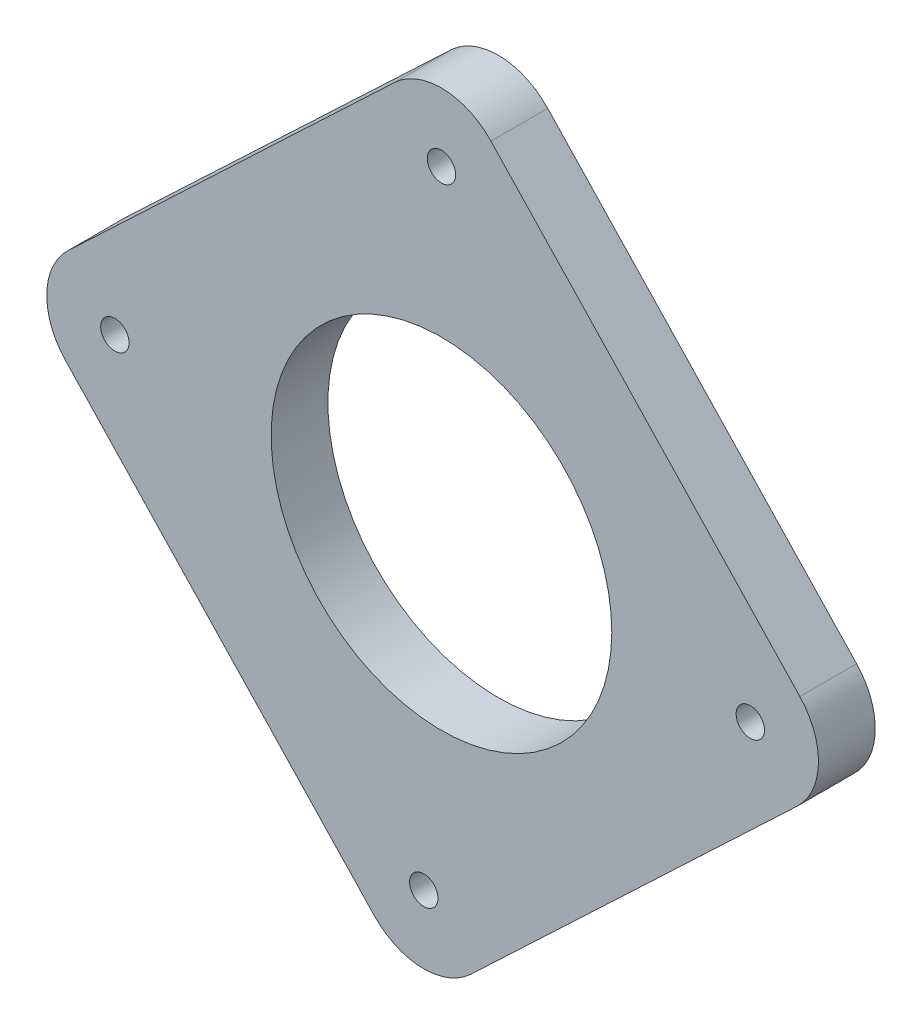
SolidWorks part; units mm, degrees
ref_plane "Front Plane" through (0, 0, 0) normal (0, 0, 1) x (1, 0, 0)
ref_plane "Top Plane" through (0, 0, 0) normal (0, 1, 0) x (1, 0, 0)
ref_plane "Right Plane" through (0, 0, 0) normal (1, 0, 0) x (0, 0, -1)
sketch "Sketch1" plane through (0, 0, 0) normal (0, 0, 1) x (1, 0, 0)
  line L0 (0, 0) -> (0, 28) construction
  line L1 (-33.1153, -3.3234) -> (-5.9149, -32.0798)
  line L2 (2.5671, -32.3157) -> (31.3234, -5.1153)
  line L3 (31.5593, 3.3667) -> (4.3589, 32.1231)
  line L4 (-4.1231, 32.3589) -> (-32.8794, 5.1586)
  circle A0 centre (0, 0) radius 15
  circle A1 centre (0, 0) radius 28 construction
  circle A2 centre (0, 28) radius 1.25
  circle A3 centre (27.2004, -0.7564) radius 1.25
  circle A4 centre (-1.556, -27.9567) radius 1.25
  circle A5 centre (-28.7564, 0.7996) radius 1.25
  arc A7 (-4.1231, 32.3589) -> (4.3589, 32.1231) centre (0, 28) cw
  arc A8 (-32.8794, 5.1586) -> (-33.1153, -3.3234) centre (-28.7564, 0.7996) ccw
  arc A9 (31.5593, 3.3667) -> (31.3234, -5.1153) centre (27.2004, -0.7564) cw
  arc A10 (-5.9149, -32.0798) -> (2.5671, -32.3157) centre (-1.556, -27.9567) ccw
  point P15 (-0.778, 0.0216)
  dimension "D1" = 30
  dimension "D2" = 56
  dimension "D3" = 2.5
  dimension "D6" = 6
  dimension "D4" = 4
extrude "Boss-Extrude1" add sketch "Sketch1" along normal blind 5
